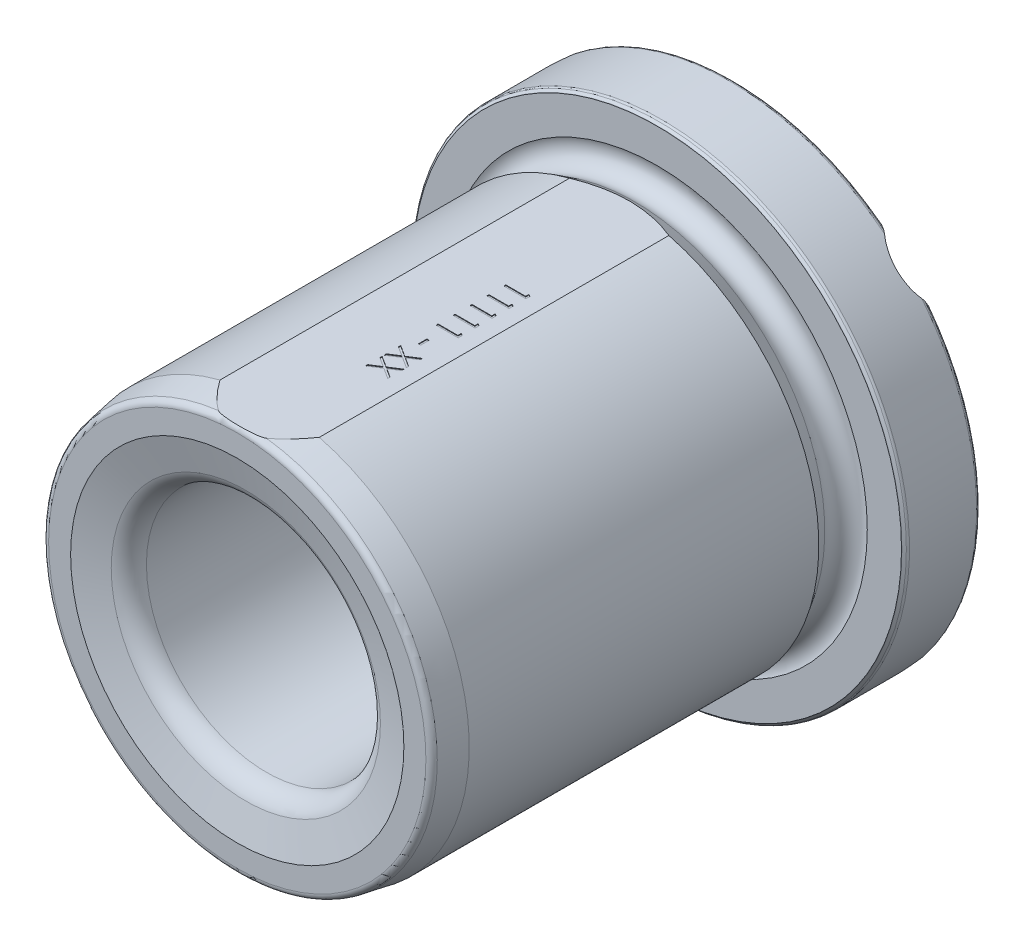
SolidWorks part; units mm, degrees
material "EN39B"
ref_plane "Front Plane" through (0, 0, 0) normal (0, 0, 1) x (1, 0, 0)
ref_plane "Top Plane" through (0, 0, 0) normal (0, 1, 0) x (1, 0, 0)
ref_plane "Right Plane" through (0, 0, 0) normal (1, 0, 0) x (0, 0, -1)
sketch "Sketch1" plane through (0, 0, 0) normal (1, 0, 0) x (0, 0, -1)
  line L0 (0, 21.5489) -> (0, 38.4429)
  line L1 (-0.9571, 39.4) -> (-11.6429, 39.4)
  line L2 (-12.5, 38.5429) -> (-12.5, 33.65)
  line L3 (-18.65, 31.8975) -> (-15.9586, 30.2441)
  line L4 (0, 0) -> (-81.5, 0) construction
  line L5 (-18.65, 31.8975) -> (-73.15, 31.8975)
  line L6 (-73.15, 31.8975) -> (-78.3236, 30.9852)
  line L7 (-79.15, 30.0004) -> (-79.15, 26.5)
  line L8 (-79.15, 26.5) -> (-77.4038, 19.9833) construction
  line L9 (-74.4949, 19.1) -> (-4.1259, 19.1)
  line L10 (-3.8891, 19.1596) -> (-0.2633, 21.1085)
  line L11 (-11.9964, 39.2536) -> (-12.3536, 38.8964)
  line L12 (-0.1464, 38.7964) -> (-0.6036, 39.2536)
  line L13 (-79.15, 26.45) -> (-77.8757, 21.6941)
  line L14 (-79.15, 26.5) -> (-79.15, 26.45)
  arc A0 (-12.5, 33.65) -> (-15.9586, 30.2441) centre (-14.65, 32.3743) cw
  arc A1 (-79.15, 30.0004) -> (-78.3236, 30.9852) centre (-78.15, 30.0004) cw
  arc A2 (-74.4949, 19.1) -> (-77.8757, 21.6941) centre (-74.4949, 22.6) cw
  arc A3 (0, 38.4429) -> (-0.1464, 38.7964) centre (-0.5, 38.4429) ccw
  arc A4 (-0.9571, 39.4) -> (-0.6036, 39.2536) centre (-0.9571, 38.9) cw
  arc A5 (-11.6429, 39.4) -> (-11.9964, 39.2536) centre (-11.6429, 38.9) ccw
  arc A6 (-12.5, 38.5429) -> (-12.3536, 38.8964) centre (-12, 38.5429) cw
  arc A7 (0, 21.5489) -> (-0.2633, 21.1085) centre (-0.5, 21.5489) cw
  arc A8 (-4.1259, 19.1) -> (-3.8891, 19.1596) centre (-4.1259, 19.6) ccw
  point P1 (0, 39.4)
  point P3 (-12.5, 39.4)
  point P27 (0, 38.65)
  point P30 (-0.75, 39.4)
  point P33 (-11.85, 39.4)
  point P36 (-12.5, 38.75)
  point P39 (0, 21.25)
  point P42 (-4, 19.1)
  dimension "D4" = 2.5
  dimension "D5" = 67.3
  dimension "D13" = 1
  dimension "D15" = 3.5
  dimension "D16" = 38.2
  dimension "D19" = 0.5
  dimension "D9" = 0.5
  dimension "D1" = 79.15
  dimension "D2" = 12.5
  dimension "D3" = 60.5
  dimension "D6" = 78.8
  dimension "D7" = 63.795
  dimension "D8" = 42.5
  dimension "D10" = 4
  dimension "D11" = 10
  dimension "D12" = 6
  dimension "D14" = 52.9
  dimension "D17" = 15
  dimension "D18" = 53
  dimension "D22" = 0.35
revolve "Revolve1" add sketch "Sketch1" angle 360 about L4
sketch "Sketch2" plane through (0, 0, 79.15) normal (0, 0, 1) x (1, 0, 0)
  line L0 (0, 0) -> (9.6855, 0) construction
  line L1 (-11.2777, 39.6395) -> (12.4718, 39.6395)
  line L2 (-11.2777, 39.6395) -> (-11.2777, 30.75)
  line L3 (-11.2777, 30.75) -> (12.4718, 30.75)
  line L4 (12.4718, 39.6395) -> (12.4718, 30.75)
  dimension "D1" = 61.5
extrude "Cut-Extrude1" cut sketch "Sketch2" against normal blind 63.5
mirror "Mirror1" about plane through (0, 0, 0) normal (0, 1, 0) of "Cut-Extrude1"
ref_axis "Axis1" through (0, 0, 18.65) along (0, 0, 1)
ref_plane "Plane1" through (0, 0, 0) normal (0.7071, 0.7071, 0) x (0, 0, -1)
sketch "Sketch5" plane through (0, 30.75, 0) normal (0, 1, 0) x (1, 0, 0)
  line L0 (1.7358, -21.2066) -> (1.7358, -76.4016) construction
  text T0 "11111 - XX"
extrude "PARTNO" cut sketch "Sketch5" against normal blind 0.1
sketch "Sketch4" plane through (0, 0, 0) normal (0.7071, 0.7071, 0) x (0, 0, -1)
  line L0 (0, -38.65) -> (0, 38.65) construction
  circle A0 centre (5.85, 0) radius 8
  dimension "D1" = 16
  dimension "D2" = 5.85
extrude "Cut-Extrude2" cut sketch "Sketch4" against normal blind 66
pattern_circular "CirPattern1" count 4 over 360 about axis through (0, 0, 18.65) along (0, 0, 1) of "Cut-Extrude2"
sketch "Sketch3" plane through (0, 0, 0) normal (1, 0, 0) x (0, 0, -1)
  line L0 (0, 0) -> (-93.6888, 0) construction
  line L1 (-79.15, 26.5) -> (-76.7507, 17.5458)
  line L2 (-79.15, 26.5) -> (-77.4038, 19.9833) construction
  line L3 (-79.15, 26.5) -> (-79.15, 31.7475)
  line L4 (-79.15, 31.7475) -> (-13.88, 31.7475)
  line L5 (-12.38, 33.2475) -> (-12.38, 40.9238)
  line L6 (-12.38, 40.9238) -> (-0.15, 40.9238)
  line L7 (-0.15, 40.9238) -> (-0.15, 17.5458)
  line L8 (-0.15, 17.5458) -> (-76.7507, 17.5458)
  line L10 (-91.0993, 50.6619) -> (12.7673, 50.6619)
  line L11 (-91.0993, 50.6619) -> (-91.0993, 9.8003)
  line L12 (-91.0993, 9.8003) -> (12.7673, 9.8003)
  line L13 (12.7673, 50.6619) -> (12.7673, 9.8003)
  arc A0 (-12.38, 33.2475) -> (-13.88, 31.7475) centre (-13.88, 33.2475) cw
  arc A1 (-15.9586, 30.2441) -> (-12.5, 33.65) centre (-14.65, 32.3743) ccw construction
  dimension "D7" = 1.5
  dimension "D1" = 0.23
  dimension "D2" = 63.495
  dimension "D3" = 53
  dimension "D4" = 15
  dimension "D5" = 79
  dimension "D6" = 12.23
  dimension "D8" = 35.0917
  dimension "D9" = 19.6005
  dimension "D10" = 12.9173
  dimension "D11" = 11.9493
  dimension "D12" = 101.3238
  dimension "D13" = 81.8476
revolve "Cut-Revolve1" cut sketch "Sketch3" angle 360 about L0
sketch "Sketch6" [suppressed] plane through (0, 0, 79.15) normal (0, 0, 1) x (1, 0, 0)
  line L1 (0, 0) -> (47.2749, 0)
  line L2 (0, 0) -> (0, 42.4875)
  line L3 (0, 42.4875) -> (47.2749, 42.4875)
  line L4 (47.2749, 0) -> (47.2749, 42.4875)
extrude "Cut-Extrude3" [suppressed] cut sketch "Sketch6" against normal through all
